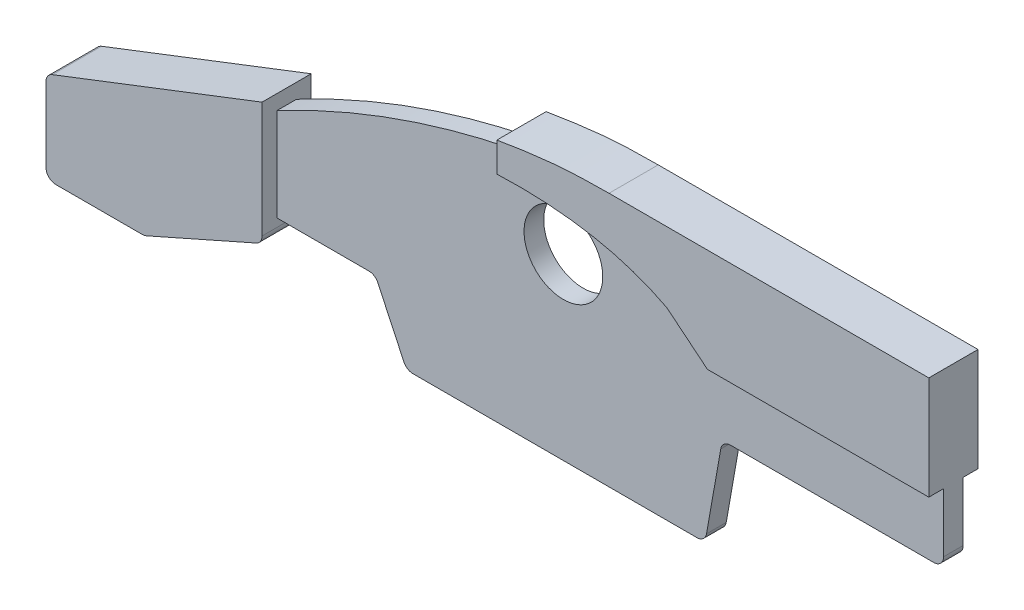
SolidWorks part; units mm, degrees
ref_plane "前视基准面" through (0, 0, 0) normal (0, 0, 1) x (1, 0, 0)
ref_plane "上视基准面" through (0, 0, 0) normal (0, 1, 0) x (1, 0, 0)
ref_plane "右视基准面" through (0, 0, 0) normal (1, 0, 0) x (0, 0, -1)
other "Configuration Table"
sketch "草图1" plane through (0, 0, 0) normal (0, 0, 1) x (1, 0, 0)
  line L0 (-68.0844, 0) -> (-36.425, 0) construction
  line L2 (-56.425, 0) -> (-36.425, 0)
  line L3 (74.5525, 0) -> (78.0254, 19.6962)
  line L4 (13.8722, 0) -> (48.5102, 0) construction
  line L5 (13.8722, 0) -> (78.575, 0)
  line L6 (13.8722, 0) -> (7.4893, 13.5957)
  line L7 (7.4893, 13.5957) -> (-12.5107, 13.5957)
  line L8 (-12.5107, 13.5957) -> (-12.5107, 10.5957)
  line L9 (-36.425, 0) -> (-12.5107, 10.5957)
  line L10 (-56.425, 0) -> (-56.425, 18.5)
  line L11 (78.0254, 19.6962) -> (123.0254, 19.6962)
  line L12 (-56.425, 18.5) -> (-12.5107, 35.4678)
  line L13 (-12.5107, 35.4678) -> (-12.5107, 32.4678)
  line L14 (123.0254, 19.6962) -> (123.0254, 54.6962)
  line L15 (123.0254, 54.6962) -> (58.0254, 54.6962)
  line L18 (35.2337, 49.6709) -> (35.2337, 52.6709)
  circle A0 centre (45.7473, 36.3494) radius 8
  spline S0 degree 2 poles (35.2337, 49.6709) (10.5743, 44.7202) (-12.5107, 32.4678) knots 0 0 0 1 1 1
  spline S1 degree 3 poles (58.0254, 54.6962) (48.8979, 54.6922) (43.1769, 53.9889) (35.2337, 52.6709) knots 0 0 0 0 1 1 1 1
  point P22 (44.3765, 39.3651)
  point P23 (45.7473, 36.3494)
extrude "凸台-拉伸1" add sketch "草图1" along normal blind 10 contours L15 S1 L18 S0 L13 L12 L10 L2 L9 L8 L7 L6 L5 L3 L11 L14 A0
sketch "草图2" plane through (0, 0, 10) normal (0, 0, 1) x (1, 0, 0)
  line L0 (-12.5107, 32.4678) -> (-12.5107, 13.5957)
  line L1 (-12.5107, 13.5957) -> (7.4893, 13.5957)
  line L2 (7.4893, 13.5957) -> (13.8722, 0)
  line L3 (13.8722, 0) -> (74.5525, 0)
  line L4 (74.5525, 0) -> (78.0254, 19.6962)
  line L5 (78.0254, 19.6962) -> (123.0254, 19.6962)
  line L6 (123.0254, 19.6962) -> (123.0254, 33.6962)
  line L7 (123.0254, 19.6962) -> (123.0254, 54.6962) construction
  line L8 (123.0254, 33.6962) -> (78.0254, 33.6962)
  line L9 (35.2337, 49.6709) -> (35.2337, 46.6709)
  parabola Q0 (35.2337, 49.6709) -> (-12.5107, 32.4678) focus (50.7184, -33.5917) apex (32.8705, 49.1789) construction
  spline S0 degree 2 poles (35.2337, 46.6709) (56.2543, 47.513) (69.7689, 40.4339) knots 0 0 0 1 1 1
  spline S1 degree 3 poles (69.7689, 40.4339) (72.2584, 38.4023) (75.2044, 35.9983) (78.0254, 33.6962) knots 0 0 0 0 1 1 1 1
  spline S2 degree 2 poles (-12.5107, 32.4678) (10.1076, 45.6432) (35.2337, 49.6709) knots 0 0 0 1 1 1
  point P23 (35.1289, 49.6498)
extrude "切除-拉伸2" cut sketch "草图2" against normal blind 3
sketch "草图3" plane through (0, 0, 0) normal (0, 0, -1) x (-1, 0, 0)
  line L0 (-123.0254, 19.6962) -> (-78.0254, 19.6962)
  line L1 (-78.0254, 19.6962) -> (-74.5525, 0)
  line L2 (-74.5525, 0) -> (-13.8722, 0)
  line L3 (-13.8722, 0) -> (-7.4893, 13.5957)
  line L4 (-7.4893, 13.5957) -> (12.5107, 13.5957)
  line L5 (12.5107, 13.5957) -> (12.5107, 32.4678)
  line L6 (-123.0254, 19.6962) -> (-123.0254, 33.6962)
  line L7 (-123.0254, 19.6962) -> (-123.0254, 54.6962) construction
  line L8 (-123.0254, 33.6962) -> (-78.0254, 33.6962)
  line L9 (-35.2337, 49.6709) -> (-35.2337, 46.6703)
  spline S0 degree 2 poles (-35.2337, 46.6703) (-53.574, 48.0361) (-69.589, 41.4282) knots 0 0 0 1 1 1
  spline S1 degree 2 poles (-69.589, 41.4282) (-74.3391, 38.2383) (-78.0254, 33.6962) knots 0 0 0 1 1 1
  spline S2 degree 2 poles (-35.2337, 49.6709) (-9.6462, 44.9317) (12.5107, 32.4678) knots 0 0 0 1 1 1
extrude "切除-拉伸3" cut sketch "草图3" against normal blind 3
fillet "圆角1" radius 2 9 edges at (78.0254, 19.6962, 5) (123.0254, 19.6962, 5) (7.4893, 13.5957, 5) (-12.5107, 10.5957, 5) (-56.425, 18.5, 5) (-56.425, 0, 5) (-36.425, 0, 5) (13.8722, 0, 5) (74.5525, 0, 5)
